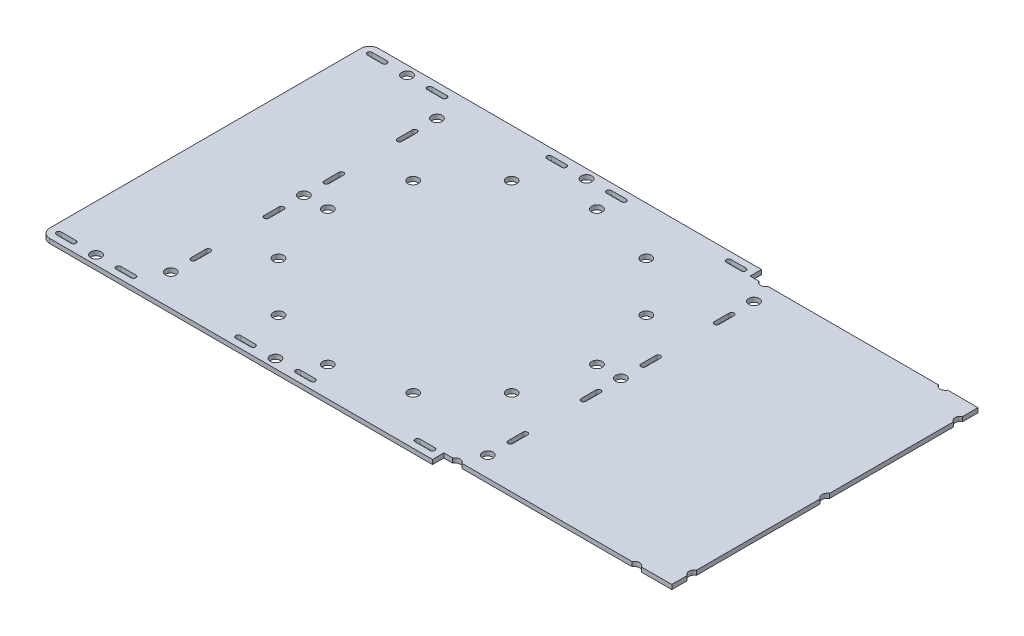
SolidWorks part; units mm, degrees
material "3.3535 (EN-AW 5754)"
ref_plane "Front Plane" through (0, 0, 0) normal (0, 0, 1) x (1, 0, 0)
ref_plane "Top Plane" through (0, 0, 0) normal (0, 1, 0) x (1, 0, 0)
ref_plane "Right Plane" through (0, 0, 0) normal (1, 0, 0) x (0, 0, -1)
sketch "Sketch1" plane through (0, 0, 0) normal (0, 1, 0) x (1, 0, 0)
  line L0 (0, 55) -> (125, 55)
  line L1 (125, 55) -> (125, -55)
  line L2 (125, -55) -> (0, -55)
  line L3 (0, 55) -> (-86, 55)
  line L4 (-86, 55) -> (-86, -55)
  line L5 (-86, -55) -> (0, -55)
  circle A0 centre (0, 0) radius 45 construction
  arc A1 (0, 55) -> (0, -55) centre (0, 0) ccw construction
  circle A2 centre (0, 45) radius 1.75
  circle A3 centre (22.5, 38.9711) radius 1.75
  circle A4 centre (38.9711, 22.5) radius 1.75
  circle A5 centre (45, 0) radius 1.75
  circle A6 centre (38.9711, -22.5) radius 1.75
  circle A7 centre (22.5, -38.9711) radius 1.75
  circle A8 centre (0, -45) radius 1.75
  circle A9 centre (-22.5, -38.9711) radius 1.75
  circle A10 centre (-38.9711, -22.5) radius 1.75
  circle A11 centre (-45, 0) radius 1.75
  circle A12 centre (-38.9711, 22.5) radius 1.75
  circle A13 centre (-22.5, 38.9711) radius 1.75
  point P31 (0, 0)
  dimension "D1" = 90
  dimension "D2" = 110
  dimension "D3" = 3.5
  dimension "D5" = 125
  dimension "D6" = 211
  dimension "D4" = 12
extrude "Boss-Extrude1" add sketch "Sketch1" along normal blind 1.5
sketch "Sketch2" plane through (0, 1.5, 0) normal (0, 1, 0) x (1, 0, 0)
  line L0 (109.5, -52) -> (49.5, -52) construction
  line L1 (49.5, -52) -> (-10.5, -52) construction
  line L2 (122, -7.5) -> (122, 7.5) construction
  line L3 (-86, -55) -> (125, -55) construction
  line L4 (-70.5, -52) -> (-10.5, -52) construction
  line L5 (-83, -52) -> (-78, -52) construction
  line L6 (-83, -51.2) -> (-78, -51.2)
  line L7 (-83, -52.8) -> (-78, -52.8)
  line L8 (-70.5, -52) -> (-70.5, -44.6063) construction
  line L9 (-58, -52) -> (-63, -52) construction
  line L10 (-58, -51.2) -> (-63, -51.2)
  line L11 (-58, -52.8) -> (-63, -52.8)
  line L12 (-23, -52) -> (-18, -52) construction
  line L13 (-23, -51.2) -> (-18, -51.2)
  line L14 (-23, -52.8) -> (-18, -52.8)
  line L15 (2, -52) -> (-3, -52) construction
  line L16 (2, -51.2) -> (-3, -51.2)
  line L17 (2, -52.8) -> (-3, -52.8)
  line L18 (37, -52) -> (42, -52) construction
  line L19 (37, -51.2) -> (42, -51.2)
  line L20 (37, -52.8) -> (42, -52.8)
  line L21 (62, -52) -> (57, -52) construction
  line L22 (62, -51.2) -> (57, -51.2)
  line L23 (62, -52.8) -> (57, -52.8)
  line L24 (97, -52) -> (102, -52) construction
  line L25 (97, -51.2) -> (102, -51.2)
  line L26 (97, -52.8) -> (102, -52.8)
  line L27 (122, -52) -> (117, -52) construction
  line L28 (122, -51.2) -> (117, -51.2)
  line L29 (122, -52.8) -> (117, -52.8)
  line L31 (117, -52) -> (102, -52) construction
  line L32 (122, -7.5) -> (122, -12.5) construction
  line L33 (122.8, -7.5) -> (122.8, -12.5)
  line L34 (121.2, -7.5) -> (121.2, -12.5)
  line L35 (122, -32) -> (122, -37) construction
  line L36 (122.8, -32) -> (122.8, -37)
  line L37 (121.2, -32) -> (121.2, -37)
  line L38 (122, -52) -> (122, -37) construction
  line L39 (87.5, -52) -> (87.5, -17.5004) construction
  line L40 (53, -52) -> (53, -37) construction
  line L41 (53, -7.5) -> (53, 7.5) construction
  line L42 (53, -32) -> (53, -37) construction
  line L43 (52.2, -32) -> (52.2, -37)
  line L44 (53.8, -32) -> (53.8, -37)
  line L45 (53, -7.5) -> (53, -12.5) construction
  line L46 (52.2, -7.5) -> (52.2, -12.5)
  line L47 (53.8, -7.5) -> (53.8, -12.5)
  line L48 (0, 0) -> (0, 14.2656) construction
  line L49 (-53, -7.5) -> (-53, 7.5) construction
  line L50 (-86, 55) -> (-86, -55) construction
  line L51 (-53, -7.5) -> (-53, -12.5) construction
  line L52 (-52.2, -7.5) -> (-52.2, -12.5)
  line L53 (-53.8, -7.5) -> (-53.8, -12.5)
  line L54 (-53, -32) -> (-53, -37) construction
  line L55 (-52.2, -32) -> (-52.2, -37)
  line L56 (-53.8, -32) -> (-53.8, -37)
  circle A0 centre (-10.5, -52) radius 1.75
  circle A1 centre (49.5, -52) radius 1.75
  circle A2 centre (109.5, -52) radius 1.75
  circle A3 centre (0, 0) radius 50 construction
  circle A4 centre (-70.5, -52) radius 1.75
  arc A5 (-83, -51.2) -> (-83, -52.8) centre (-83, -52) ccw
  arc A6 (-78, -52.8) -> (-78, -51.2) centre (-78, -52) ccw
  arc A7 (-58, -51.2) -> (-58, -52.8) centre (-58, -52) cw
  arc A8 (-63, -52.8) -> (-63, -51.2) centre (-63, -52) cw
  arc A9 (-23, -51.2) -> (-23, -52.8) centre (-23, -52) ccw
  arc A10 (-18, -52.8) -> (-18, -51.2) centre (-18, -52) ccw
  arc A11 (2, -51.2) -> (2, -52.8) centre (2, -52) cw
  arc A12 (-3, -52.8) -> (-3, -51.2) centre (-3, -52) cw
  arc A13 (37, -51.2) -> (37, -52.8) centre (37, -52) ccw
  arc A14 (42, -52.8) -> (42, -51.2) centre (42, -52) ccw
  arc A15 (62, -51.2) -> (62, -52.8) centre (62, -52) cw
  arc A16 (57, -52.8) -> (57, -51.2) centre (57, -52) cw
  arc A17 (97, -51.2) -> (97, -52.8) centre (97, -52) ccw
  arc A18 (102, -52.8) -> (102, -51.2) centre (102, -52) ccw
  arc A19 (122, -51.2) -> (122, -52.8) centre (122, -52) cw
  arc A20 (117, -52.8) -> (117, -51.2) centre (117, -52) cw
  circle A21 centre (122, -44.5) radius 1.75
  circle A22 centre (122, 0) radius 1.75
  arc A23 (122.8, -7.5) -> (121.2, -7.5) centre (122, -7.5) ccw
  arc A24 (121.2, -12.5) -> (122.8, -12.5) centre (122, -12.5) ccw
  arc A25 (122.8, -32) -> (121.2, -32) centre (122, -32) ccw
  arc A26 (121.2, -37) -> (122.8, -37) centre (122, -37) ccw
  circle A27 centre (53, 0) radius 1.75
  circle A28 centre (53, -44.5) radius 1.75
  arc A29 (52.2, -32) -> (53.8, -32) centre (53, -32) cw
  arc A30 (53.8, -37) -> (52.2, -37) centre (53, -37) cw
  arc A31 (52.2, -7.5) -> (53.8, -7.5) centre (53, -7.5) cw
  arc A32 (53.8, -12.5) -> (52.2, -12.5) centre (53, -12.5) cw
  circle A33 centre (-53, -44.5) radius 1.75
  circle A34 centre (-53, 0) radius 1.75
  arc A35 (-52.2, -7.5) -> (-53.8, -7.5) centre (-53, -7.5) ccw
  arc A36 (-53.8, -12.5) -> (-52.2, -12.5) centre (-53, -12.5) ccw
  arc A37 (-52.2, -32) -> (-53.8, -32) centre (-53, -32) ccw
  arc A38 (-53.8, -37) -> (-52.2, -37) centre (-53, -37) ccw
  point P8 (0, 0)
  point P17 (-80.5, -52)
  point P25 (-60.5, -52)
  point P34 (-20.5, -52)
  point P41 (-0.5, -52)
  point P48 (39.5, -52)
  point P55 (59.5, -52)
  point P62 (99.5, -52)
  point P69 (119.5, -52)
  point P80 (122, -10)
  point P85 (122, -34.5)
  point P107 (53, -34.5)
  point P113 (53, -10)
  point P128 (-53, -10)
  point P134 (-53, -34.5)
  point P139 (-52.5, -52)
  dimension "D1" = 3.5
  dimension "D5" = 100
  dimension "D6" = 0.8
  dimension "D2" = 3
  dimension "D3" = 3
  dimension "D4" = 60
  dimension "D7" = 10
  dimension "D8" = 5
  dimension "D10" = 106
  dimension "D9" = 4
extrude "Cut-Extrude1" cut sketch "Sketch2" against normal blind 3
fillet "Fillet1" radius 3 4 edges at (-86, 0.75, -55) (125, 0.75, -55) (125, 0.75, 55) (-86, 0.75, 55)
mirror "Mirror1" about plane through (0, 0, 0) normal (0, 0, 1) of "Cut-Extrude1"
sketch "Sketch3" plane through (0, 1.5, 0) normal (0, 1, 0) x (1, 0, 0)
  line L0 (56.2913, 40.066) -> (56.2913, -33.2396)
  line L1 (61.8353, -34.8296) -> (107.6513, 38.476)
  line L2 (105.1073, 43.066) -> (59.2913, 43.066)
  line L3 (57, -44.5) -> (57, -52) construction
  line L4 (57, -52) -> (49.5, -52) construction
  line L5 (57, -52) -> (122, 52) construction
  line L7 (67.64, -44.41) -> (113.456, 28.8956)
  line L9 (119, 27.3056) -> (119, -46)
  line L10 (116, -49) -> (70.184, -49)
  line L11 (125, -52) -> (125, 52) construction
  arc A0 (67.64, -44.41) -> (70.184, -49) centre (70.184, -46) ccw
  arc A1 (119, -46) -> (116, -49) centre (116, -46) cw
  arc A2 (119, 27.3056) -> (113.456, 28.8956) centre (116, 27.3056) ccw
  arc A3 (107.6513, 38.476) -> (105.1073, 43.066) centre (105.1073, 40.066) ccw
  arc A4 (56.2913, -33.2396) -> (61.8353, -34.8296) centre (59.2913, -33.2396) ccw
  arc A5 (56.2913, 40.066) -> (59.2913, 43.066) centre (59.2913, 40.066) cw
  circle A7 centre (0, 0) radius 40
  point P17 (64.7712, -49)
  point P22 (119, 37.766)
  point P25 (110.52, 43.066)
  point P28 (56.2913, -43.7)
  dimension "D4" = 3
  dimension "D5" = 80
  dimension "D1" = 3
  dimension "D2" = 10
  dimension "D3" = 6
extrude "Cut-Extrude2" [suppressed] cut sketch "Sketch3" against normal blind 3
sketch "Sketch4" plane through (0, 1.5, 0) normal (0, 1, 0) x (1, 0, 0)
  line L0 (125, -52) -> (125, 52) construction
  line L1 (125, -51.2) -> (45, -51.2)
  line L2 (125, -51.2) -> (125, -55)
  line L3 (125, -55) -> (45, -55)
  line L4 (45, -51.2) -> (45, -55)
  line L5 (-83, -55) -> (122, -55) construction
  line L6 (122, 55) -> (-83, 55) construction
  line L7 (45, 55) -> (125, 55)
  line L8 (45, 55) -> (45, 51.2)
  line L9 (45, 51.2) -> (125, 51.2)
  line L10 (125, 55) -> (125, 51.2)
  dimension "D1" = 80
  dimension "D2" = 3.8
extrude "Cut-Extrude3" cut sketch "Sketch4" against normal blind 1.5
sketch "Sketch5" plane through (0, 1.5, 0) normal (0, 1, 0) x (1, 0, 0)
  line L1 (125, 51.2) -> (121.2, 51.2)
  line L2 (125, 51.2) -> (125, -51.25)
  line L3 (125, -51.25) -> (121.2, -51.25)
  line L4 (121.2, 51.2) -> (121.2, -51.25)
  dimension "D1" = 3.8
extrude "Cut-Extrude4" cut sketch "Sketch5" against normal blind 1.5
